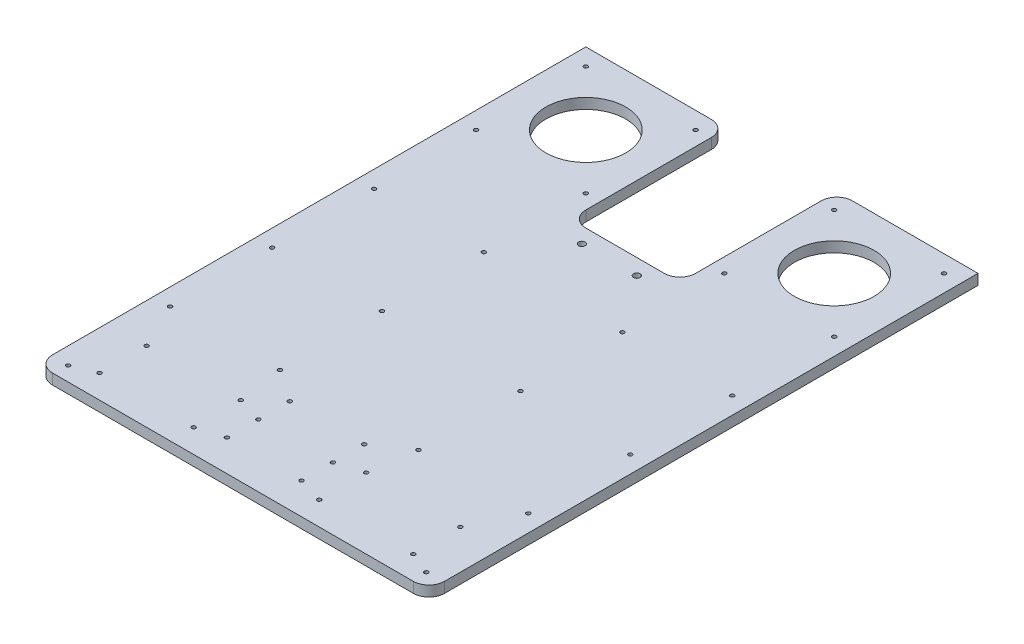
SolidWorks part; units mm, degrees
ref_plane "Front Plane" through (0, 0, 0) normal (0, 0, 1) x (1, 0, 0)
ref_plane "Top Plane" through (0, 0, 0) normal (0, 1, 0) x (1, 0, 0)
ref_plane "Right Plane" through (0, 0, 0) normal (1, 0, 0) x (0, 0, -1)
sketch "Sketch1" plane through (0, 0, 0) normal (0, 1, 0) x (1, 0, 0)
  line L0 (0, 210) -> (0, -210) construction
  line L1 (-150, -210) -> (150, -210)
  line L2 (-150, -210) -> (-150, 210)
  line L3 (-150, 210) -> (-42, 210)
  line L4 (150, -210) -> (150, 210)
  line L5 (-150, -210) -> (150, 210) construction
  line L6 (-150, 210) -> (150, -210) construction
  line L7 (-28.5, -138) -> (-28.5, -162) construction
  line L8 (-28.5, -162) -> (-28.5, -186) construction
  line L9 (-137, 210) -> (-137, -210) construction
  line L10 (-42, 210) -> (-42, 90)
  line L11 (-42, 90) -> (0, 90)
  line L12 (0, 90) -> (42, 90)
  line L13 (42, 90) -> (42, 210)
  line L14 (42, 210) -> (150, 210)
  line L15 (-53, 210) -> (-53, -210) construction
  line L17 (-120, -192) -> (-48, -192) construction
  line L18 (-120, -192) -> (-120, -156) construction
  line L19 (-120, -156) -> (-48, -156) construction
  line L20 (-48, -192) -> (-48, -156) construction
  line L21 (-120, -192) -> (-48, -156) construction
  line L22 (-120, -156) -> (-48, -192) construction
  circle A8 centre (-21, 78) radius 2.5
  circle A9 centre (21, 78) radius 2.5
  circle A10 centre (-28.5, -138) radius 1.5
  circle A11 centre (-28.5, -162) radius 1.5
  circle A12 centre (-28.5, -186) radius 1.5
  circle A13 centre (28.5, -186) radius 1.5
  circle A14 centre (28.5, -162) radius 1.5
  circle A15 centre (28.5, -138) radius 1.5
  circle A16 centre (-95, 155) radius 30.5
  circle A17 centre (-95, 155) radius 50 construction
  circle A18 centre (-137, 197) radius 1.5
  circle A19 centre (-53, 197) radius 1.5
  circle A20 centre (-53, 113) radius 1.5
  circle A21 centre (-137, 113) radius 1.5
  circle A22 centre (-137, 35) radius 1.5
  circle A23 centre (-137, -43) radius 1.5
  circle A24 centre (-137, -121) radius 1.5
  circle A25 centre (137, -121) radius 1.5
  circle A26 centre (137, -43) radius 1.5
  circle A27 centre (137, 35) radius 1.5
  circle A28 centre (53, 197) radius 1.5
  circle A29 centre (137, 197) radius 1.5
  circle A30 centre (137, 113) radius 1.5
  circle A31 centre (95, 155) radius 30.5
  circle A32 centre (53, 113) radius 1.5
  circle A33 centre (-53, 35) radius 1.5
  circle A34 centre (-53, -43) radius 1.5
  circle A35 centre (-53, -121) radius 1.5
  circle A36 centre (53, -121) radius 1.5
  circle A38 centre (53, -43) radius 1.5
  circle A40 centre (53, 35) radius 1.5
  circle A41 centre (-137, -199) radius 1.5
  circle A42 centre (137, -199) radius 1.5
  circle A43 centre (-120, -192) radius 1.5
  circle A44 centre (-48, -192) radius 1.5
  circle A45 centre (-48, -156) radius 1.5
  circle A46 centre (-120, -156) radius 1.5
  circle A47 centre (48, -156) radius 1.5
  circle A48 centre (48, -192) radius 1.5
  circle A49 centre (120, -192) radius 1.5
  circle A50 centre (120, -156) radius 1.5
  point P0 (0, 0)
  point P48 (-95, 155)
  point P83 (-84, -174)
  dimension "D4" = 3
  dimension "D5" = 28.5
  dimension "D6" = 72
  dimension "D8" = 5
  dimension "D9" = 21
  dimension "D10" = 12
  dimension "D7" = 61
  dimension "D11" = 100
  dimension "D16" = 3
  dimension "D19" = 55
  dimension "D22" = 78
  dimension "D23" = 78
  dimension "D25" = 84
  dimension "D26" = 78
  dimension "D27" = 3
  dimension "D1" = 300
  dimension "D2" = 420
  dimension "D3" = 24
  dimension "D12" = 13
  dimension "D13" = 84
  dimension "D14" = 120
  dimension "D15" = 84
  dimension "D17" = 42
  dimension "D20" = 55
  dimension "D21" = 78
  dimension "D24" = 2
  dimension "D28" = 84
  dimension "D29" = 36
  dimension "D30" = 72
  dimension "D31" = 36
  dimension "D18" = 4
extrude "Boss-Extrude1" add sketch "Sketch1" along normal blind 8
fillet "Fillet1" radius 12 6 edges at (150, 4, 210) (-150, 4, 210) (42, 4, -210) (42, 4, -90) (-42, 4, -90) (-42, 4, -210)
